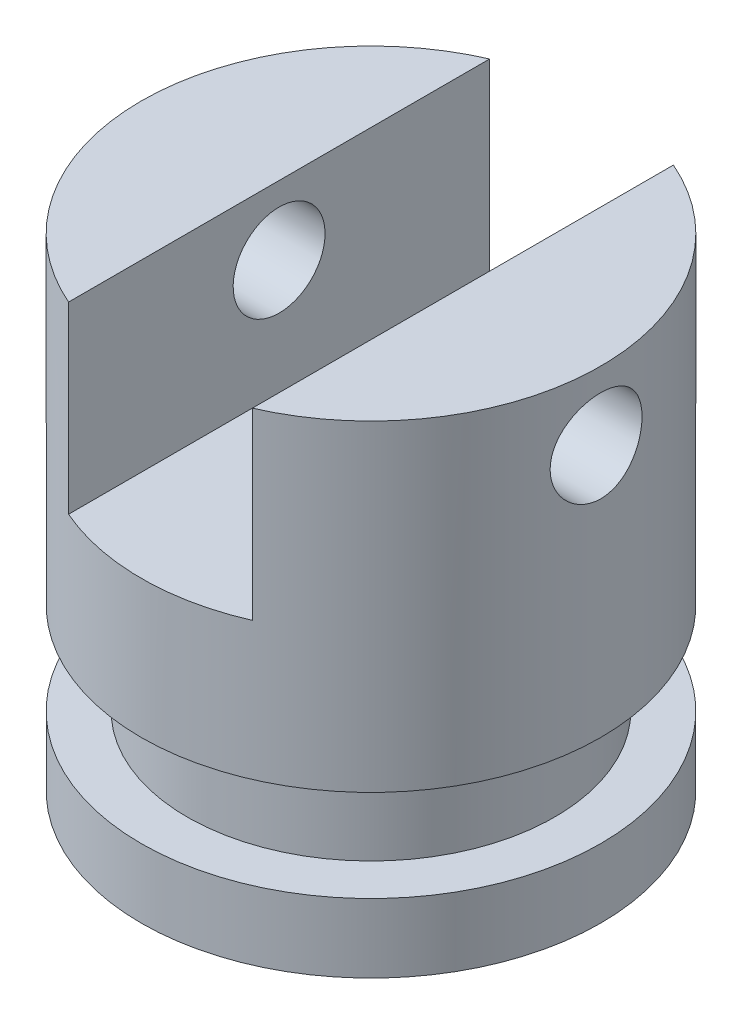
SolidWorks part; units mm, degrees
material "1060 Alloy"
ref_plane "Front Plane" through (0, 0, 0) normal (0, 0, 1) x (1, 0, 0)
ref_plane "Top Plane" through (0, 0, 0) normal (0, 1, 0) x (1, 0, 0)
ref_plane "Right Plane" through (0, 0, 0) normal (1, 0, 0) x (0, 0, -1)
sketch "Sketch2" plane through (0, 0, 0) normal (0, 0, 1) x (1, 0, 0)
  line L0 (0, 0) -> (5, 0)
  line L1 (5, 0) -> (5, 1.5)
  line L2 (5, 1.5) -> (4, 1.5)
  line L3 (4, 1.5) -> (4, 3.5)
  line L4 (4, 3.5) -> (5, 3.5)
  line L5 (5, 3.5) -> (5, 10.5)
  line L6 (5, 10.5) -> (0, 10.5)
  line L7 (0, 10.5) -> (0, 0)
  dimension "D1" = 5
  dimension "D2" = 10.5
  dimension "D3" = 1
  dimension "D4" = 2
  dimension "D5" = 1.5
revolve "Revolve1" add sketch "Sketch2" angle 360 about L7
sketch "Sketch3" plane through (0, 10.5, 0) normal (0, 1, 0) x (1, 0, 0)
  line L0 (-2, 4.5826) -> (-2, -4.5826)
  line L1 (2, -4.5826) -> (2, 4.5826)
  circle A1 centre (0, 0) radius 5 construction
  arc A2 (-2, -4.5826) -> (2, -4.5826) centre (0, 0) ccw
  arc A3 (-2, 4.5826) -> (2, 4.5826) centre (0, 0) cw
  dimension "D1" = 4
extrude "Cut-Extrude1" cut sketch "Sketch3" against normal blind 4
sketch "Sketch4" plane through (-2, 0, 0) normal (1, 0, 0) x (0, 0, -1)
  line L0 (4.5826, 10.5) -> (-4.5826, 10.5) construction
  point P0 (0, 9)
  dimension "D1" = 1.5
ref_plane "Plane1" through (5, 0, 0) normal (1, 0, 0) x (0, 0, -1)
sketch "Sketch6" plane through (5, 0, 0) normal (1, 0, 0) x (0, 0, -1)
  point P0 (0, 9)
hole_wizard "Ø2.0mm Dowel Hole1" positions "Sketch6" profile "Sketch7" hole size "Ø2.0" standard "ANSI Metric" end condition through all
sketch "Sketch7" plane through (5, 9, 0) normal (0, 1, 0) x (0, 0, -1)
  line L0 (0, 0) -> (0, 10)
  line L1 (0, 10) -> (1, 10)
  line L2 (1, 10) -> (1, 0)
  line L5 (1, 0) -> (0, 0)
  line L11 (0, -6.35) -> (0, 107.95) construction
  dimension "Thru Hole Dia." = 2
  dimension "Thru Hole Depth" = 10
